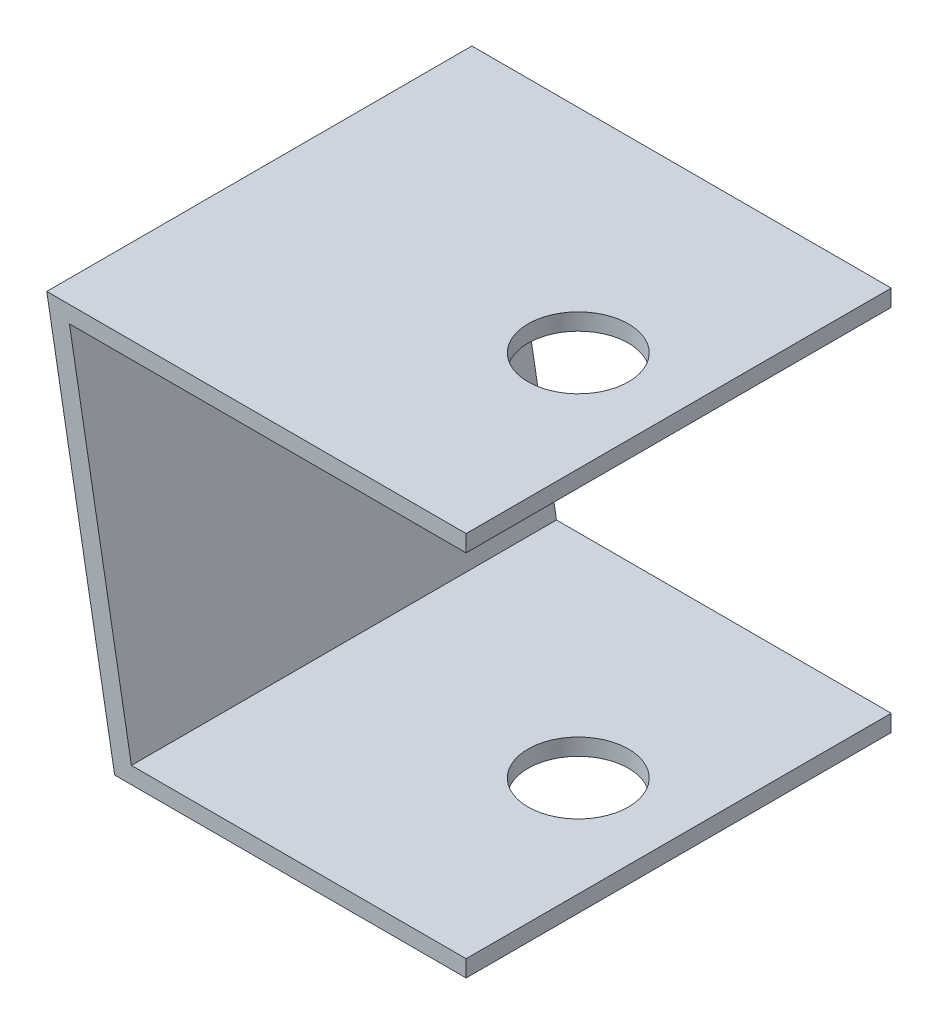
SolidWorks part; units mm, degrees
ref_plane "Front Plane" through (0, 0, 0) normal (0, 0, 1) x (1, 0, 0)
ref_plane "Top Plane" through (0, 0, 0) normal (0, 1, 0) x (1, 0, 0)
ref_plane "Right Plane" through (0, 0, 0) normal (1, 0, 0) x (0, 0, -1)
ref_plane "Plane1" through (0, 151.6764, 0) normal (0, 1, 0) x (1, 0, 0)
sketch "Sketch1" plane through (0, 0, 0) normal (0, 0, 1) x (1, 0, 0)
  line L0 (15, 152.9264) -> (-35, 152.9264)
  line L1 (-35, 152.9264) -> (-35, 100.4264)
  line L2 (-35, 100.4264) -> (15, 100.4264)
  line L3 (15, 100.4264) -> (15, 97.9264)
  line L4 (15, 97.9264) -> (-37.5, 97.9264)
  line L5 (-37.5, 97.9264) -> (-37.5, 155.4264)
  line L6 (-37.5, 155.4264) -> (15, 155.4264)
  line L7 (15, 155.4264) -> (15, 152.9264)
  line L8 (-35, 100.4264) -> (-37.5, 100.4264) construction
  line L9 (0, 23.8568) -> (0, 255.9335) construction
  line L10 (15, 152.9264) -> (0, 126.6764) construction
  line L11 (0, 126.6764) -> (15, 100.4264) construction
  dimension "D1" = 57.5
  dimension "D2" = 2.5
  dimension "D3" = 37.5
  dimension "D4" = 15
extrude "Boss-Extrude1" add sketch "Sketch1" along normal mid plane 63.5
sketch "Sketch2" plane through (0, 0, 31.75) normal (0, 0, 1) x (1, 0, 0)
  line L0 (-37.5, 97.9264) -> (-47.6388, 155.4264)
  line L1 (-47.6388, 155.4264) -> (-37.5, 155.4264)
  line L3 (-37.5, 155.4264) -> (-37.5, 97.9264)
  line L4 (15, 155.4264) -> (-37.5, 155.4264) construction
  dimension "D1" = 80
extrude "Boss-Extrude3" add sketch "Sketch2" against normal up to vertex (63.5 mm away)
sketch "Sketch3" plane through (0, 0, 31.75) normal (0, 0, 1) x (1, 0, 0)
  line L0 (-35, 152.9264) -> (-44.2572, 152.9264)
  line L1 (-44.2572, 152.9264) -> (-35, 100.4264)
  line L2 (-35, 100.4264) -> (-35, 152.9264)
  line L3 (-47.6388, 155.4264) -> (-37.5, 97.9264) construction
extrude "Cut-Extrude1" cut sketch "Sketch3" against normal through all
sketch "Sketch4" plane through (0, 155.4264, 0) normal (0, 1, 0) x (1, 0, 0)
  circle A0 centre (0, 0) radius 7.5
  circle A1 centre (0, 0) radius 12.5 construction
  dimension "D1" = 15
extrude "Cut-Extrude2" cut sketch "Sketch4" against normal through all
